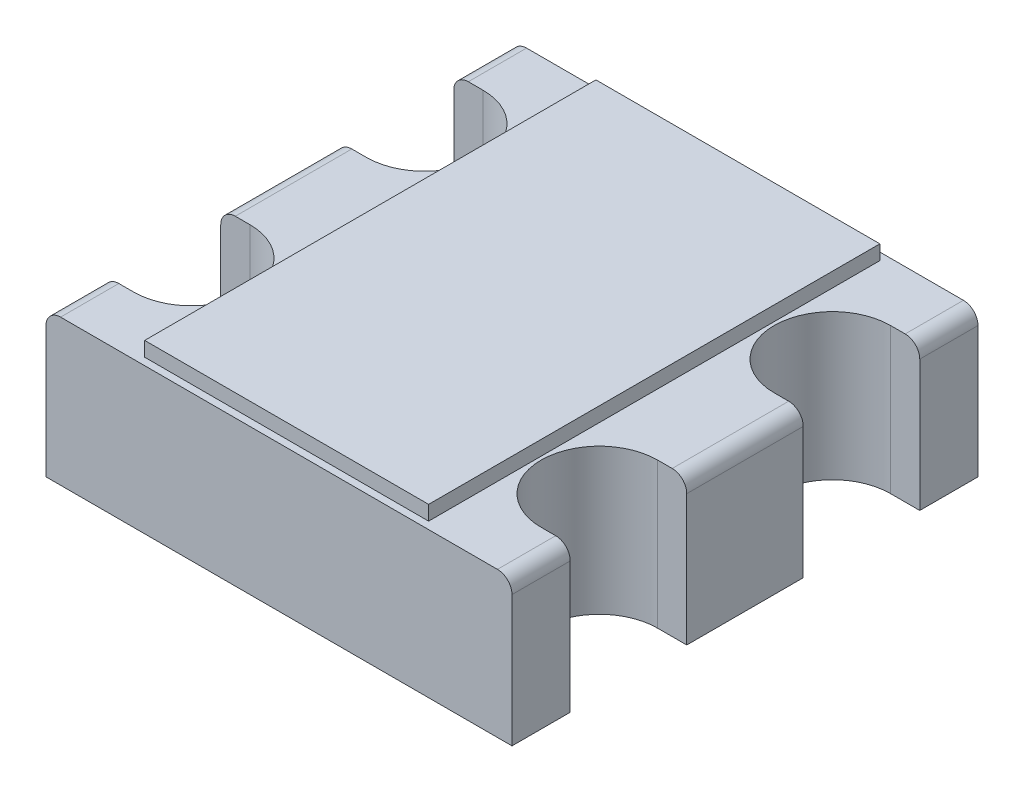
SolidWorks part; units mm, degrees
ref_plane "Front Plane" through (0, 0, 0) normal (0, 0, 1) x (1, 0, 0)
ref_plane "Top Plane" through (0, 0, 0) normal (0, 1, 0) x (1, 0, 0)
ref_plane "Right Plane" through (0, 0, 0) normal (1, 0, 0) x (0, 0, -1)
sketch "Sketch1" plane through (0, 0, 0) normal (0, 1, 0) x (1, 0, 0)
  line L0 (0, 2.3267) -> (0, -2.2841) construction
  line L1 (-2.4335, 0) -> (1.9212, 0) construction
  line L3 (-0.8, 0.8) -> (-0.8, 0.6)
  line L4 (-0.8, 0.6) -> (-0.7, 0.6)
  line L5 (-0.7, 0.2) -> (-0.8, 0.2)
  line L6 (-0.8, 0.2) -> (-0.8, -0.2)
  line L34 (-0.8, 0.6) -> (-0.8, 0.2862) construction
  line L37 (-0.8, 0.8) -> (0.8, 0.8)
  line L40 (0.8, 0.2) -> (0.8, -0.2)
  line L41 (0.7, 0.2) -> (0.8, 0.2)
  line L42 (0.8, 0.6) -> (0.7, 0.6)
  line L43 (0.8, 0.8) -> (0.8, 0.6)
  line L46 (0.8, -0.8) -> (0.8, -0.6)
  line L47 (0.8, -0.6) -> (0.7, -0.6)
  line L48 (0.7, -0.2) -> (0.8, -0.2)
  line L49 (-0.8, -0.8) -> (0.8, -0.8)
  line L50 (-0.7, -0.2) -> (-0.8, -0.2)
  line L51 (-0.8, -0.6) -> (-0.7, -0.6)
  line L52 (-0.8, -0.8) -> (-0.8, -0.6)
  arc A0 (-0.7, 0.6) -> (-0.7, 0.2) centre (-0.7, 0.4) cw
  arc A1 (0.7, 0.6) -> (0.7, 0.2) centre (0.7, 0.4) ccw
  arc A2 (0.7, -0.6) -> (0.7, -0.2) centre (0.7, -0.4) cw
  arc A3 (-0.7, -0.6) -> (-0.7, -0.2) centre (-0.7, -0.4) ccw
  point P5 (0, 0)
  point P11 (-0.8, 0)
  point P13 (0, -0.8)
  point P21 (0, 0.8)
  point P31 (0, 0.8)
  point P34 (0, 0.8)
  point P37 (0.8, 0)
  point P39 (-0.8, 0)
  point P61 (-0.5, 0.4)
  dimension "D4" = 0.4
  dimension "D1" = 0.4
  dimension "D2" = 0.8
  dimension "D3" = 0.8
  dimension "D6" = 0.3
extrude "Boss-Extrude1" add sketch "Sketch1" along normal blind 0.5
sketch "Sketch2" plane through (0, 0.5, 0) normal (0, 1, 0) x (1, 0, 0)
  line L1 (-0.4864, -0.7748) -> (0.4886, -0.7748)
  line L2 (-0.4864, -0.7748) -> (-0.4864, 0.7745)
  line L3 (-0.4864, 0.7745) -> (0.4886, 0.7745)
  line L4 (0.4886, -0.7748) -> (0.4886, 0.7745)
extrude "Boss-Extrude2" add sketch "Sketch2" along normal blind 0.05
fillet "Fillet2" radius 0.05 6 edges at (-0.8, 0.5, 0) (-0.8, 0.5, -0.7) (0.8, 0.5, -0.7) (0.8, 0.5, 0) (0.8, 0.5, 0.7) (-0.8, 0.5, 0.7)
